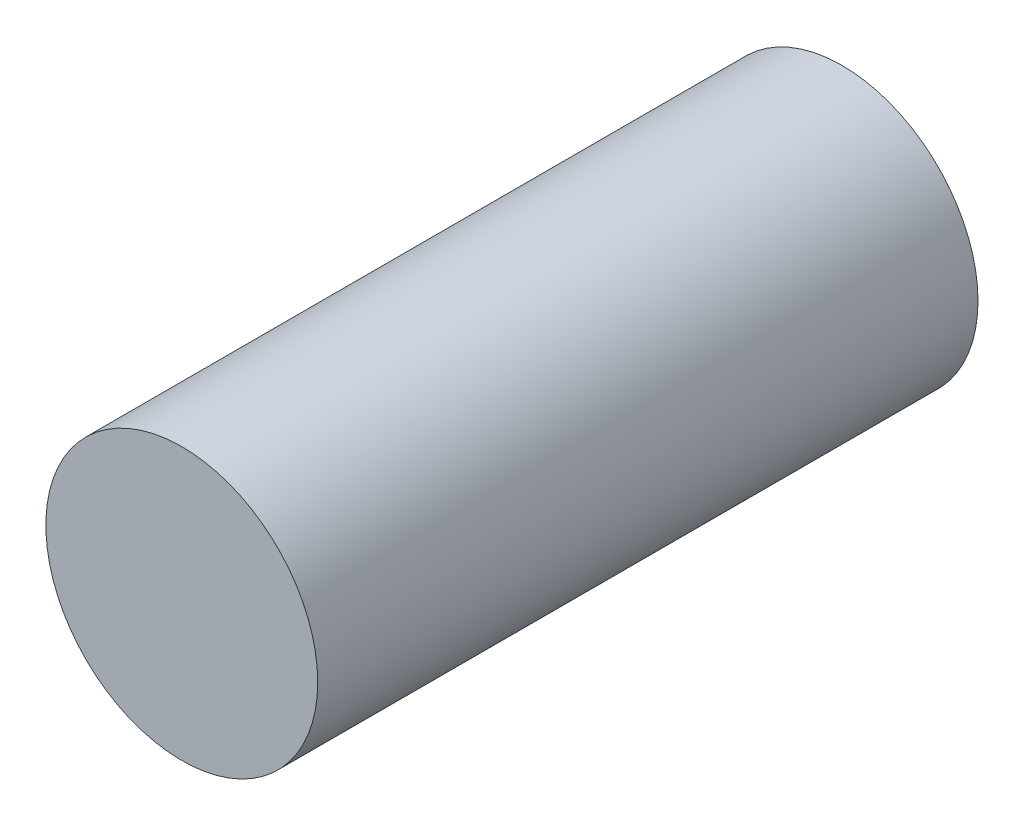
SolidWorks part; units mm, degrees
ref_plane "前视基准面" through (0, 0, 0) normal (0, 0, 1) x (1, 0, 0)
ref_plane "上视基准面" through (0, 0, 0) normal (0, 1, 0) x (1, 0, 0)
ref_plane "右视基准面" through (0, 0, 0) normal (1, 0, 0) x (0, 0, -1)
sketch "草图1" plane through (0, 0, 0) normal (0, 0, 1) x (1, 0, 0)
  circle A0 centre (0, 0) radius 3.5
  dimension "D1" = 7
extrude "凸台-拉伸1" add sketch "草图1" along normal blind 17
